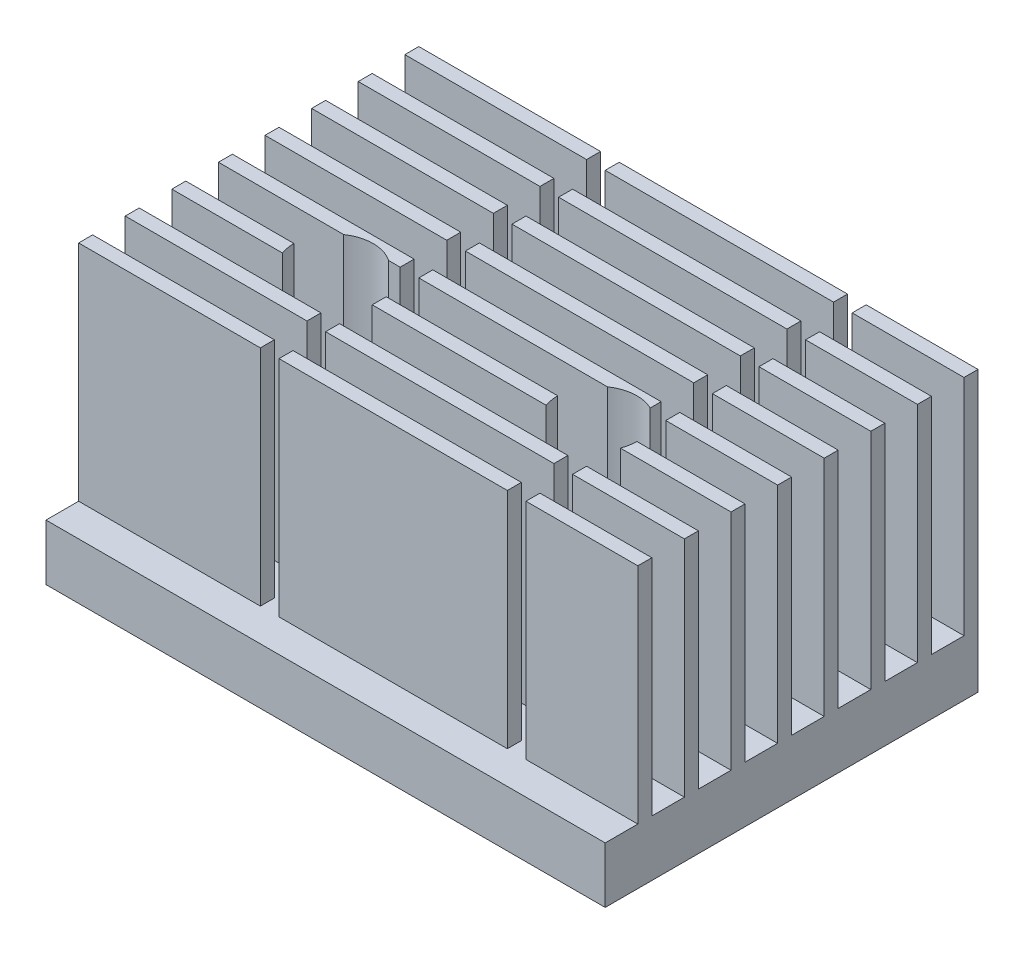
SolidWorks part; units mm, degrees
ref_plane "前视基准面" through (0, 0, 0) normal (0, 0, 1) x (1, 0, 0)
ref_plane "上视基准面" through (0, 0, 0) normal (0, 1, 0) x (1, 0, 0)
ref_plane "右视基准面" through (0, 0, 0) normal (1, 0, 0) x (0, 0, -1)
sketch "草图1" plane through (0, 0, 0) normal (0, 1, 0) x (1, 0, 0)
  line L0 (0, 37.5709) -> (0, -51.0007) construction
  line L1 (-30, 20) -> (30, 20)
  line L2 (-30, 20) -> (-30, -20)
  line L3 (-30, -20) -> (30, -20)
  line L4 (30, 20) -> (30, -20)
  line L5 (-48.656, 0) -> (59.7607, 0) construction
  dimension "D1" = 60
  dimension "D2" = 40
extrude "拉伸1" add sketch "草图1" along normal blind 30
sketch "草图2" plane through (0, 30, 0) normal (0, 1, 0) x (-1, 0, 0)
  line L0 (-30, 20) -> (-30, -20) construction
  line L1 (-30, -18.5) -> (30, -18.5)
  line L2 (-30, -18.5) -> (-30, -15)
  line L3 (-30, -15) -> (30, -15)
  line L4 (30, -18.5) -> (30, -15)
  line L5 (30, -20) -> (30, 20) construction
  line L6 (-30, -20) -> (30, -20) construction
  line L7 (-30, -13.5) -> (30, -13.5)
  line L8 (-30, -13.5) -> (-30, -10)
  line L9 (-30, -10) -> (30, -10)
  line L10 (30, -13.5) -> (30, -10)
  line L11 (-30, -8.5) -> (30, -8.5)
  line L12 (-30, -8.5) -> (-30, -5)
  line L13 (-30, -5) -> (30, -5)
  line L14 (30, -8.5) -> (30, -5)
  line L15 (-30, -3.5) -> (30, -3.5)
  line L16 (-30, -3.5) -> (-30, 0)
  line L17 (-30, 0) -> (30, 0)
  line L18 (30, -3.5) -> (30, 0)
  line L19 (-30, 1.5) -> (30, 1.5)
  line L20 (-30, 1.5) -> (-30, 5)
  line L21 (-30, 5) -> (30, 5)
  line L22 (30, 1.5) -> (30, 5)
  line L23 (-30, 6.5) -> (30, 6.5)
  line L24 (-30, 6.5) -> (-30, 10)
  line L25 (-30, 10) -> (30, 10)
  line L26 (30, 6.5) -> (30, 10)
  line L27 (-30, 11.5) -> (30, 11.5)
  line L28 (-30, 11.5) -> (-30, 15)
  line L29 (-30, 15) -> (30, 15)
  line L30 (30, 11.5) -> (30, 15)
  line L31 (-30, 16.5) -> (30, 16.5)
  line L32 (-30, 16.5) -> (-30, 20)
  line L33 (-30, 20) -> (30, 20)
  line L34 (30, 16.5) -> (30, 20)
  dimension "D1" = 3.5
  dimension "D2" = 1.5
extrude "切除-拉伸1" cut sketch "草图2" against normal offset from surface (24 mm away) 6 up to face at (0, 0, 0)
sketch "草图3" plane through (0, 30, 0) normal (0, 1, 0) x (-1, 0, 0)
  line L0 (-30, 20) -> (30, 20) construction
  line L1 (-18, 20) -> (-16, 20)
  line L2 (-18, 20) -> (-18, -20)
  line L3 (-18, -20) -> (-16, -20)
  line L4 (-16, 20) -> (-16, -20)
  line L5 (-30, -20) -> (30, -20) construction
  line L6 (-30, -18.5) -> (-30, -15) construction
  line L7 (8.5, 20) -> (10.5, 20)
  line L8 (8.5, 20) -> (8.5, -20)
  line L9 (8.5, -20) -> (10.5, -20)
  line L10 (10.5, 20) -> (10.5, -20)
  dimension "D1" = 12
  dimension "D2" = 2
extrude "切除-拉伸2" cut sketch "草图3" against normal up to surface (24 mm away) up to face at (0, 6, 3.25)
sketch "草图4" plane through (0, 0, 0) normal (0, -1, 0) x (1, 0, 0)
  line L0 (33.2472, 5) -> (-34.7303, 5) construction
  line L1 (0, 13.5955) -> (0, -13.5955) construction
  line L2 (14.15, 10.9864) -> (14.15, -11.9217) construction
  line L3 (-14.15, 10.9864) -> (-14.15, -11.9217) construction
  line L4 (-33.2472, 5) -> (34.7303, 5) construction
  line L5 (-30, 20) -> (30, 20) construction
  circle A0 centre (14.15, 5) radius 2.25
  circle A1 centre (-14.15, 5) radius 2.25
  dimension "D1" = 4.5
  dimension "D2" = 28.3
  dimension "D3" = 15
extrude "切除-拉伸3" cut sketch "草图4" against normal through all
sketch "草图5" plane through (0, 30, 0) normal (0, 1, 0) x (-1, 0, 0)
  circle A2 centre (14.15, 5) radius 4.25
  circle A3 centre (14.15, 5) radius 4.25
  circle A5 centre (-14.15, 5) radius 4.25
  circle A6 centre (-14.15, 5) radius 4.25
  dimension "D1" = 2
  dimension "D2" = 2
extrude "切除-拉伸4" cut sketch "草图5" against normal up to surface (24 mm away) up to face at (1.0889, 6, -1.2153)
